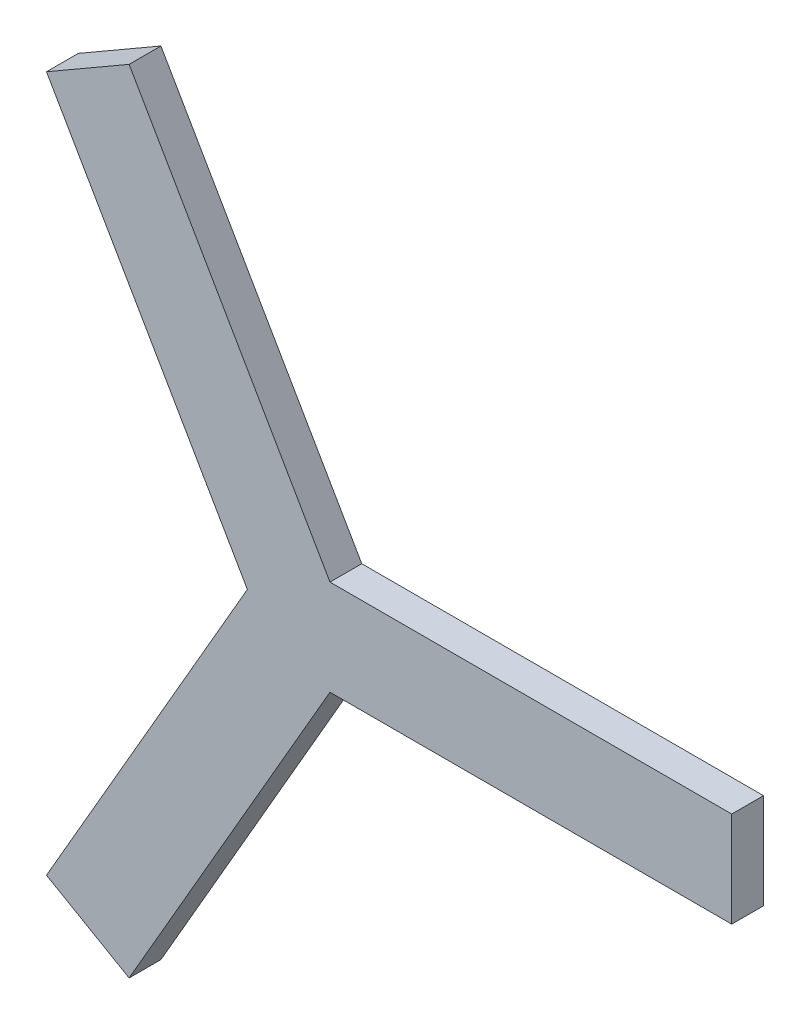
SolidWorks part; units mm, degrees
ref_plane "Front Plane" through (0, 0, 0) normal (0, 0, 1) x (1, 0, 0)
ref_plane "Top Plane" through (0, 0, 0) normal (0, 1, 0) x (1, 0, 0)
ref_plane "Right Plane" through (0, 0, 0) normal (1, 0, 0) x (0, 0, -1)
sketch "Sketch1" plane through (0, 0, 0) normal (0, 0, 1) x (1, 0, 0)
  line L7 (270, 30) -> (17.3205, 30)
  line L8 (270, 30) -> (270, -30)
  line L14 (270, -30) -> (17.3205, -30)
  line L19 (270, 30) -> (0, -30) construction
  line L20 (0, 30) -> (270, -30) construction
  line L21 (-109.0192, -248.8269) -> (17.3205, -30)
  line L22 (-109.0192, -248.8269) -> (-160.9808, -218.8269)
  line L24 (-160.9808, -218.8269) -> (-34.641, 0)
  line L25 (-109.0192, -248.8269) -> (-25.9808, 15) construction
  line L26 (25.9808, -15) -> (-160.9808, -218.8269) construction
  line L27 (-109.0192, 248.8269) -> (17.3205, 30)
  line L28 (-109.0192, 248.8269) -> (-160.9808, 218.8269)
  line L30 (-160.9808, 218.8269) -> (-34.641, 0)
  line L31 (-109.0192, 248.8269) -> (-25.9808, -15) construction
  line L32 (25.9808, 15) -> (-160.9808, 218.8269) construction
  point P2 (-125, 216.5064)
  point P6 (-125, -216.5064)
  point P7 (250, 0)
  point P9 (135, 0)
  point P10 (-67.5, -116.9134)
  point P15 (-67.5, 116.9134)
  point P20 (-135, 233.8269)
  point P25 (-135, -233.8269)
  point P27 (270, 0)
extrude "Boss-Extrude2" add sketch "Sketch1" along normal blind 20
